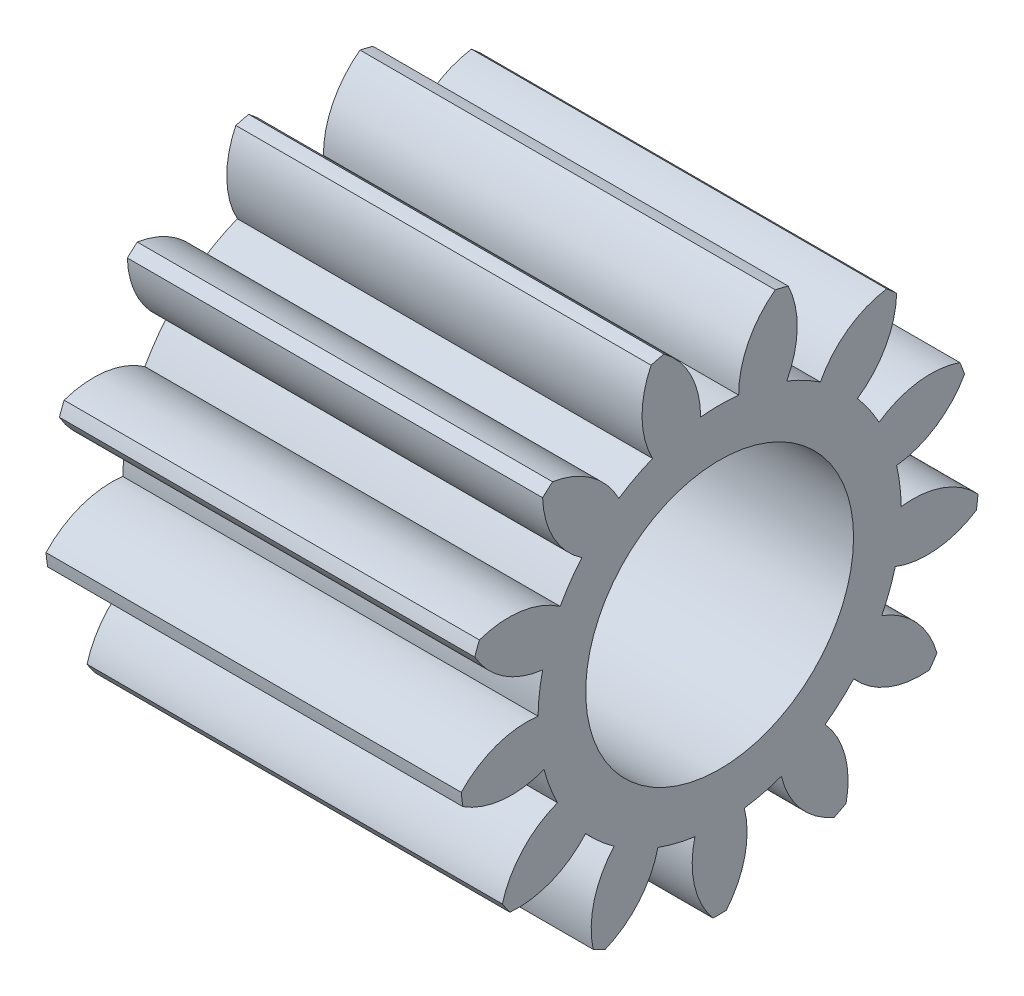
SolidWorks part; units mm, degrees
ref_plane "Plane1" through (0, 0, 0) normal (0, 0, 1) x (1, 0, 0)
ref_plane "Plane2" through (0, 0, 0) normal (0, 1, 0) x (1, 0, 0)
ref_plane "Plane3" through (0, 0, 0) normal (1, 0, 0) x (0, 0, -1)
sketch "HoldingSke" plane through (0, 0, 0) normal (0, 1, 0) x (1, 0, 0)
  line L0 (0, 0) -> (1.9487, -0.4499)
  line L1 (-15, 0) -> (100, 0) construction
  line L2 (0, 0) -> (-2.1039, 2.3779)
  line L3 (0, 0) -> (-11.863, 4.5341)
  line L4 (0, 0) -> (8.4147, 1.9427)
  line L5 (0, 0) -> (-46.8476, -17.4728)
  line L6 (0, 0) -> (-9.9476, -6.7116)
  line L7 (-2.1039, 2.3779) -> (8.6586, 51.2059)
  line L8 (-76.2, 54.61) -> (-76.1, 54.61)
  line L9 (-71.009, 38.7566) -> (-53.1078, 45.2721)
  line L10 (-76.2, 71.12) -> (104.1128, 71.12)
  line L11 (0, 0) -> (-12, 0)
  line L12 (-76.2, 101.6) -> (-76.181, 101.6)
  line L13 (24.9733, 27.94) -> (52.9518, 28.4284)
  line L14 (24.9733, 27.94) -> (24.9743, 27.94)
  line L15 (24.9733, 27.94) -> (100.4006, 29.5858)
  line L16 (-63.627, -0.5) -> (-12.827, -0.5)
  circle A0 centre (0, 0) radius 0.4
  circle A1 centre (0, 0) radius 2.624
  circle A2 centre (0, 0) radius 37.5
  circle A3 centre (0, 0) radius 0.4
  dimension "MHD" = 5.248
  dimension "Hub_dia" = 75
  dimension "Bore" = 0.8
  dimension "MBD" = 0.8
  dimension "Num_teeth" = 13
  dimension "Pitch" = 2
  dimension "Overall_len" = 50
  dimension "Show_teeth" = 13
  dimension "Thickness" = 12
  dimension "OAL" = 50.0001
  dimension "T_dim" = 0.1
  dimension "Ap" = 20
  dimension "H" = 19.05
  dimension "Pitch_radius" = 180.3128
  dimension "Width" = 12
  dimension "Backlash" = 0.019
  dimension "Addendum_fac" = 1
  dimension "Dedendum_fac" = 1.25
  dimension "Clearance_fac" = 0.25
  dimension "Dedendum_add" = 0.001
  dimension "Module" = 0.5
sketch "BasProSke" plane through (0, 0, 0) normal (0, 1, 0) x (1, 0, 0)
  line L0 (-10, 0) -> (60, 0) construction
  line L1 (0, 0) -> (0, 3.75)
  line L2 (0, 0) -> (6, 0)
  line L3 (6, 0) -> (6, 3.75)
  line L4 (6, 3.75) -> (0, 3.75)
  dimension "Thickness" = 6
  dimension "Diameter" = 7.5
revolve "Base-Revolve" add sketch "BasProSke" angle 360 about L0
sketch "TooCutSke" plane through (0, 0, 0) normal (1, 0, 0) x (0, 0, -1)
  line L1 (0, 0) -> (0, 107) construction
  line L2 (0, 0) -> (-0.425, 3.2221) construction
  line L3 (0, 0) -> (-1.5461, 6.2726) construction
  line L4 (-0.425, 3.2221) -> (-0.773, 3.1363) construction
  arc A0 (0.2752, 2.6095) -> (-0.2752, 2.6095) centre (0, 0) ccw
  arc A1 (0.8316, 3.6827) -> (-0.8316, 3.6827) centre (0, 0) ccw
  circle A2 centre (0, 0) radius 3.25 construction
  circle A3 centre (0, 0) radius 3.054 construction
  arc A4 (-0.2752, 2.6095) -> (-0.8316, 3.6827) centre (-1.5752, 2.6164) ccw
  arc A5 (0.8316, 3.6827) -> (0.2752, 2.6095) centre (1.5752, 2.6164) ccw
  dimension "Root_dia" = 5.248
  dimension "Overcut_dia" = 7.5508
  dimension "Pitch_dia" = 6.5
  dimension "Base_dia" = 6.108
  dimension "Flank_rad" = 1.3
  dimension "Half_ang" = 13.846
  dimension "Half_CT" = 0.3585
extrude "ToothCut" cut sketch "TooCutSke" along normal through all
fillet "Breaks" [suppressed] radius 0.01
fillet "RootFillets" [suppressed] radius 0.126
pattern_circular "TeethCuts" count 13 every 27.692 about axis through (-10, 0, 0) along (1, 0, 0) of "ToothCut", "RootFillets", "Breaks"
sketch "HubNeaOneSke" plane through (0, 0, 0) normal (-1, 0, 0) x (0, 0, 1)
  circle A0 centre (0, 0) radius 2.624
  dimension "Diameter" = 5.248
extrude "HubNearOne" [suppressed] add sketch "HubNeaOneSke" along normal blind 44.0001
sketch "HubNeaBotSke" plane through (0, 0, 0) normal (-1, 0, 0) x (0, 0, 1)
  circle A0 centre (0, 0) radius 2.624
  dimension "Diameter" = 5.248
extrude "HubNearBoth" [suppressed] add sketch "HubNeaBotSke" along normal blind 22
ref_plane "FarPln" through (6, 0, 0) normal (1, 0, 0) x (0, 0, -1)
sketch "HubFarSke" plane through (6, 0, 0) normal (1, 0, 0) x (0, 0, -1)
  circle A0 centre (0, 0) radius 2.624
  dimension "Diameter" = 5.248
extrude "HubFar" [suppressed] add sketch "HubFarSke" along normal blind 22
sketch "BorSke" plane through (0, 0, 0) normal (1, 0, 0) x (0, 0, -1)
  circle A0 centre (0, 0) radius 0.4
  dimension "Diameter" = 0.8
extrude "Bore" cut sketch "BorSke" along normal mid plane 100.0001
sketch "KeySke" plane through (0, 0, 0) normal (1, 0, 0) x (0, 0, -1)
  line L0 (-0.05, 0) -> (-0.05, 0.5)
  line L1 (-0.05, 0.5) -> (0.05, 0.5)
  line L2 (0.05, 0.5) -> (0.05, 0)
  line L3 (0, 0) -> (0, 34) construction
  line L4 (-0.05, 0) -> (0.05, 0)
  dimension "Offset" = 0.5
  dimension "Width" = 0.1
extrude "Keyway" [suppressed] cut sketch "KeySke" along normal mid plane 100.0001
pattern_circular "Keyway2" [suppressed] count 2 every 90 about axis through (-10, 0, 0) along (1, 0, 0)
sketch "Sketch1" plane through (0, 0, 0) normal (-1, 0, 0) x (0, 0, 1)
  circle A0 centre (0, 0) radius 3
  dimension "D1" = 6
sketch "Sketch3" plane through (0, 0, 0) normal (-1, 0, 0) x (0, 0, 1)
  circle A0 centre (0, 0) radius 3.75
extrude "Boss-Extrude3" [suppressed] add sketch "Sketch3" along normal blind 15
sketch "Sketch4" [suppressed] plane through (-15, 0, 0) normal (-1, 0, 0) x (0, 0, 1)
  line L1 (-2.5, 2.5) -> (2.5, 2.5)
  line L2 (-2.5, 2.5) -> (-2.5, -2.5)
  line L3 (-2.5, -2.5) -> (2.5, -2.5)
  line L4 (2.5, 2.5) -> (2.5, -2.5)
  line L5 (-2.5, 2.5) -> (2.5, -2.5) construction
  line L6 (-2.5, -2.5) -> (2.5, 2.5) construction
  point P0 (0, 0)
  dimension "D1" = 5
  dimension "D2" = 5
extrude "Boss-Extrude4" [suppressed] add sketch "Sketch4" along normal blind 10
sketch "Sketch5" plane through (6, 0, 0) normal (1, 0, 0) x (0, 0, -1)
  circle A0 centre (0, 0) radius 3.75
extrude "Boss-Extrude5" [suppressed] add sketch "Sketch5" along normal blind 15
sketch "Sketch6" plane through (6, 0, 0) normal (1, 0, 0) x (0, 0, -1)
  circle A0 centre (0, 0) radius 1.935
  dimension "D1" = 3.87
extrude "Cut-Extrude1" cut sketch "Sketch6" against normal blind 5
equation "' \"Module@HoldingSke\" = 6.35"
equation "' \"Num_teeth@HoldingSke\" = 12"
equation "' \"Ap@HoldingSke\" =  20"
equation "' \"Ap@HoldingSke\" = 20"
equation "' \"Width@HoldingSke\" = 0.5 * 25.4"
equation "' \"Hub_dia@HoldingSke\"= 1 * 25.4"
equation "' \"Hub_dia@HoldingSke\" = 1 * 25.4"
equation "' \"Overall_len@HoldingSke\" = 1.0 * 25.4"
equation "' \"Bore@HoldingSke\" = 0.75 * 25.4"
equation "' \"T_dim@HoldingSke\" = 0.1 * 25.4"
equation "' \"Width@KeySke\" = 0.25 * 25.4"
equation "' \"Show_teeth@HoldingSke\" = 13"
equation "' \"Backlash@HoldingSke\" = 0.009 * 25.4"
equation "' \"Addendum_fac@HoldingSke\" = 1.0"
equation "' \"Dedendum_fac@HoldingSke\" = 1.25"
equation "' \"Dedendum_add@HoldingSke\" = 0.00005 * 25.4"
equation "' \"Clearance_fac@HoldingSke\" = 0.25"
equation "\"Pitch@HoldingSke\" = 1 / \"Module@HoldingSke\""
equation "\"Overcut_dia@TooCutSke\" = (\"Num_teeth@HoldingSke\" + 2 * \"Addendum_fac@HoldingSke\") / \"Pitch@HoldingSke\" + 0.002 * 25.4"
equation "\"Pitch_dia@TooCutSke\" = \"Num_teeth@HoldingSke\" / \"Pitch@HoldingSke\""
equation "\"Base_dia@TooCutSke\" = \"Num_teeth@HoldingSke\" / \"Pitch@HoldingSke\" * cos((\"Ap@HoldingSke\"  * 3.14159265 / 180))"
equation "\"Root_dia@TooCutSke\" = (\"Num_teeth@HoldingSke\" + 2) / \"Pitch@HoldingSke\" - 2 * (\"Addendum_fac@HoldingSke\" + \"Dedendum_fac@HoldingSke\") / \"Pitch@HoldingSke\" - \"Dedendum_add@HoldingSke\" * 2"
equation "\"Half_ang@TooCutSke\" = 180 / \"Num_teeth@HoldingSke\""
equation "\"Half_CT@TooCutSke\" = \"Num_teeth@HoldingSke\" / \"Pitch@HoldingSke\" * sin((3.14159265 / 2 / \"Num_teeth@HoldingSke\")) / 2 - 7 * \"Backlash@HoldingSke\" / 4"
equation "\"Flank_rad@TooCutSke\" = \"Num_teeth@HoldingSke\" / \"Pitch@HoldingSke\" / 5"
equation "\"Radius@RootFillets\" = \"Clearance_fac@HoldingSke\" / \"Pitch@HoldingSke\" + \"Dedendum_add@HoldingSke\""
equation "\"Break_rad@Breaks\" = 0.02 / \"Pitch@HoldingSke\""
equation "\"Thickness@HoldingSke\" = \"Width@HoldingSke\""
equation "\"OAL@HoldingSke\" = \"Thickness@HoldingSke\""
equation "\"MHD@HoldingSke\" = (\"Num_teeth@HoldingSke\" + 2) / \"Pitch@HoldingSke\" - 2 * (\"Addendum_fac@HoldingSke\" + \"Dedendum_fac@HoldingSke\")  / \"Pitch@HoldingSke\" - \"Dedendum_add@HoldingSke\" * 2"
equation "\"MBD@HoldingSke\" = (\"Num_teeth@HoldingSke\" + 2) / \"Pitch@HoldingSke\" - 2 * (\"Addendum_fac@HoldingSke\" + \"Dedendum_fac@HoldingSke\")  / \"Pitch@HoldingSke\" - \"Dedendum_add@HoldingSke\" * 2 - 0.002 * 25.4"
equation "\"MHD@HoldingSke\" = ((sgn( \"MHD@HoldingSke\" - \"Hub_dia@HoldingSke\" )-1)*( \"MHD@HoldingSke\" - \"Hub_dia@HoldingSke\" ))/-2+ \"Hub_dia@HoldingSke\""
equation "\"MBD@HoldingSke\" = ((sgn( \"MBD@HoldingSke\" - \"Bore@HoldingSke\" )-1)*( \"MBD@HoldingSke\" - \"Bore@HoldingSke\" ))/-2+ \"Bore@HoldingSke\""
equation "\"OAL@HoldingSke\" = ((sgn( \"OAL@HoldingSke\" - \"Overall_len@HoldingSke\" )+1)*( \"OAL@HoldingSke\" - \"Overall_len@HoldingSke\" ))/2 + \"Overall_len@HoldingSke\" + 0.000002 * 25.4"
equation "\"Num_teeth@TeethCuts\" = int( \"Show_teeth@HoldingSke\" ) + 1"
equation "\"Num_teeth@TeethCuts\" = ((sgn( \"Num_teeth@TeethCuts\" - \"Num_teeth@HoldingSke\" )-1)*( \"Num_teeth@TeethCuts\" - \"Num_teeth@HoldingSke\" ))/-2+ \"Num_teeth@HoldingSke\""
equation "\"Num_teeth@TeethCuts\" = ((sgn( \"Num_teeth@TeethCuts\" - 2.0)+1)*( \"Num_teeth@TeethCuts\" - 2.0))/2 +2.0"
equation "\"Angle@TeethCuts\" = 360.0 / \"Num_teeth@HoldingSke\""
equation "\"Diameter@BasProSke\" = (\"Num_teeth@HoldingSke\" + 2 * \"Addendum_fac@HoldingSke\") / \"Pitch@HoldingSke\""
equation "\"Thickness@BasProSke\"=6"
equation "' \"Fillet_rad@BasProSke\" =  \"Thickness@HoldingSke\" * 0.05"
equation "' \"Fillet_rad@BasProSke\" = \"Thickness@HoldingSke\" * 0.05"
equation "\"MHD@HoldingSke\" = ((sgn( \"MHD@HoldingSke\" - \"Root_dia@TooCutSke\" )-1)*( \"MHD@HoldingSke\" - \"Root_dia@TooCutSke\" ))/-2+ \"Root_dia@TooCutSke\""
equation "\"Diameter@HubNeaOneSke\" = \"MHD@HoldingSke\""
equation "\"Length@HubNearOne\" = \"OAL@HoldingSke\" - \"Thickness@BasProSke\""
equation "\"Diameter@HubNeaBotSke\" = \"MHD@HoldingSke\""
equation "\"Length@HubNearBoth\" = ( \"OAL@HoldingSke\" - \"Thickness@BasProSke\" ) / 2.0"
equation "\"Thickness@FarPln\" = \"Thickness@BasProSke\""
equation "\"Diameter@HubFarSke\" = \"MHD@HoldingSke\""
equation "\"Length@HubFar\" = ( \"OAL@HoldingSke\" - \"Thickness@BasProSke\" ) / 2.0"
equation "\"Diameter@BorSke\" = \"MBD@HoldingSke\""
equation "\"D1@Bore\" = \"OAL@HoldingSke\" * 2.0"
equation "\"D1@Keyway\" = \"OAL@HoldingSke\" * 2.0"
equation "\"Offset@KeySke\" = \"T_dim@HoldingSke\" + \"MBD@HoldingSke\" / 2.0"
